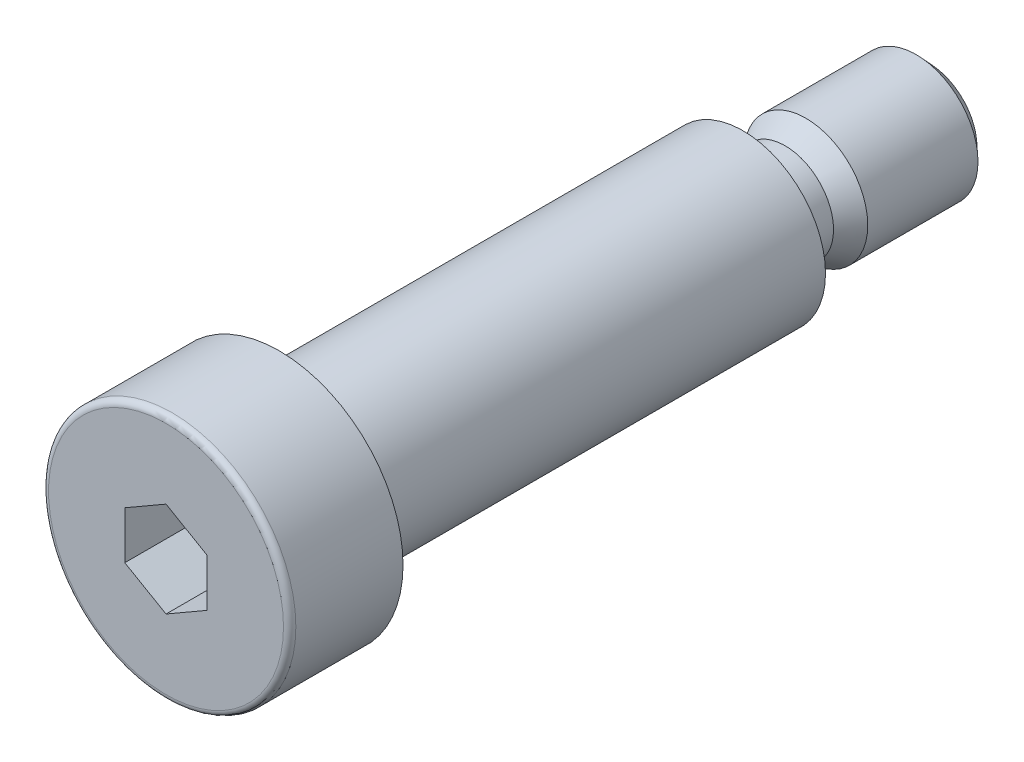
SolidWorks part; units mm, degrees
material "1.0545 (S355N)"
ref_plane "Płaszczyzna przednia" through (0, 0, 0) normal (0, 0, 1) x (1, 0, 0)
ref_plane "Płaszczyzna górna" through (0, 0, 0) normal (0, 1, 0) x (1, 0, 0)
ref_plane "Płaszczyzna prawa" through (0, 0, 0) normal (1, 0, 0) x (0, 0, -1)
sketch "Szkic1" plane through (0, 0, 0) normal (0, 1, 0) x (1, 0, 0)
  line L0 (6, 28.6) -> (4.7, 26.58)
  line L1 (12, -33.5) -> (-12, -33.5)
  line L2 (12, -33.5) -> (12, -22.5)
  line L3 (12, -22.5) -> (-12, -22.5)
  line L4 (-12, -33.5) -> (-12, -22.5)
  line L5 (8, -22.5) -> (-8, -22.5)
  line L6 (8, -22.5) -> (8, 22.5)
  line L7 (8, 22.5) -> (-8, 22.5)
  line L8 (-8, -22.5) -> (-8, 22.5)
  line L9 (-4.7, 22.5) -> (4.7, 22.5)
  line L10 (-4.7, 22.5) -> (-4.7, 26.58)
  line L11 (-4.7, 26.58) -> (4.7, 26.58)
  line L12 (4.7, 22.5) -> (4.7, 26.58)
  line L13 (6, 28.6) -> (6, 39.3)
  line L14 (6, 39.3) -> (4.7, 40.5)
  line L15 (4.7, 40.5) -> (-4.7, 40.5)
  line L16 (-4.7, 40.5) -> (-6, 39.3)
  line L17 (-6, 39.3) -> (-6, 28.6)
  line L18 (-6, 28.6) -> (-4.7, 26.58)
  line L19 (6, 28.6) -> (-6, 28.6) construction
  line L20 (6, 39.3) -> (-6, 39.3) construction
  line L21 (0, -19.9356) -> (0, 25.6583) construction
  line L22 (0, -33.5) -> (0, 40.5)
  point P4 (0, -22.5)
  point P14 (0, -22.5)
  point P15 (0, 22.5)
  point P16 (0, 22.5)
  point P17 (-8, 0)
  point P23 (0, 28.6)
  point P25 (0, 40.5)
  point P26 (0, 26.58)
  point P27 (0, 39.3)
  dimension "D1" = 24
  dimension "D2" = 11
  dimension "D3" = 16
  dimension "l1" = 45
  dimension "D5" = 9.4
  dimension "D6" = 18
  dimension "D7" = 12
  dimension "D8" = 9.4
  dimension "D9" = 1.2
  dimension "D10" = 2.02
  dimension "D11" = 10.7
revolve "Obrót1" add sketch "Szkic1" angle 360 about L22
sketch "Szkic2" plane through (0, 0, 33.5) normal (0, 0, 1) x (1, 0, 0)
  line L1 (4, 2.3094) -> (0, 4.6188)
  line L2 (0, 4.6188) -> (-4, 2.3094)
  line L3 (-4, 2.3094) -> (-4, -2.3094)
  line L4 (-4, -2.3094) -> (0, -4.6188)
  line L5 (0, -4.6188) -> (4, -2.3094)
  line L6 (4, -2.3094) -> (4, 2.3094)
  circle A0 centre (0, 0) radius 4 construction
  dimension "D1" = 8
extrude "Wytnij-wyciągnięcie1" cut sketch "Szkic2" against normal blind 6.6
fillet "Zaokrąglenie1" radius 0.6 1 edges at (12, 0, 33.5)
